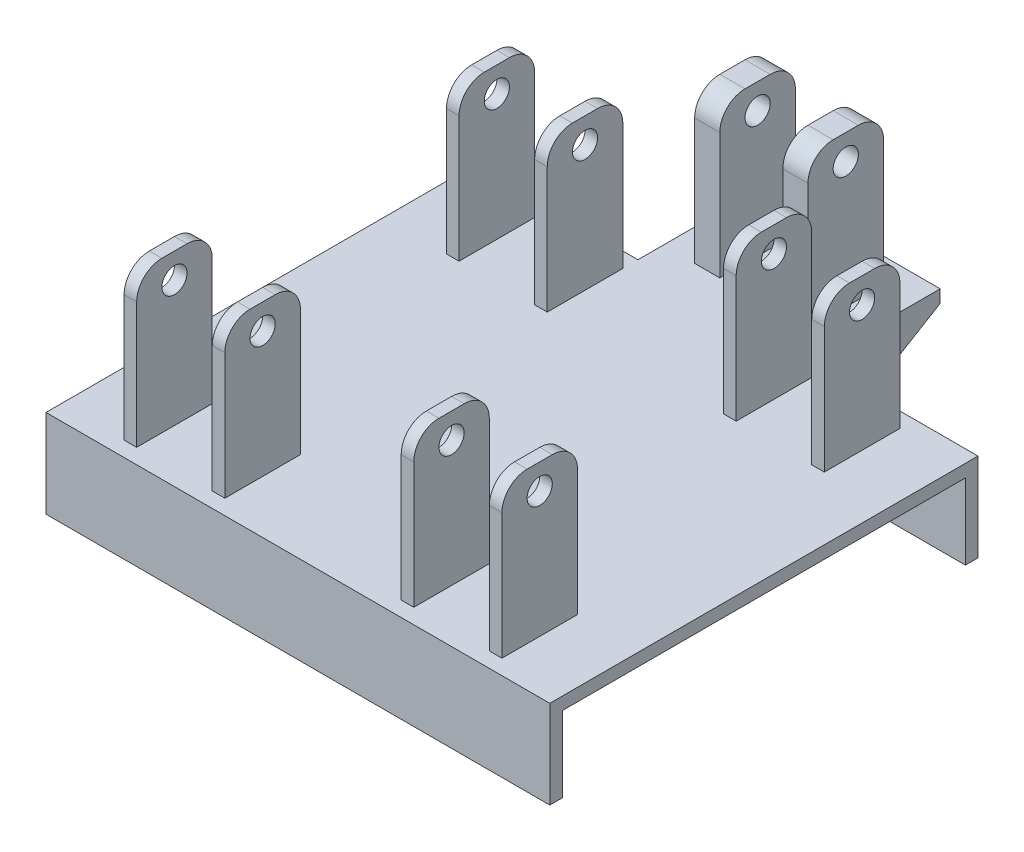
SolidWorks part; units mm, degrees
ref_plane "Front Plane" through (0, 0, 0) normal (0, 0, 1) x (1, 0, 0)
ref_plane "Top Plane" through (0, 0, 0) normal (0, 1, 0) x (1, 0, 0)
ref_plane "Right Plane" through (0, 0, 0) normal (1, 0, 0) x (0, 0, -1)
sketch "Sketch2" plane through (0, 0, 0) normal (0, 1, 0) x (1, 0, 0)
  line L1 (-100, -80) -> (100, -80)
  line L2 (-100, -80) -> (-100, 80)
  line L3 (-100, 80) -> (100, 80)
  line L4 (100, -80) -> (100, 80)
  line L5 (-100, -80) -> (100, 80) construction
  line L6 (-100, 80) -> (100, -80) construction
  point P0 (0, 0)
  dimension "D1" = 160
  dimension "D2" = 200
extrude "Boss-Extrude1" add sketch "Sketch2" along normal blind 5
sketch "Sketch3" plane through (0, 5, 0) normal (0, 1, 0) x (1, 0, 0)
  line L1 (-75, 78.9876) -> (-70, 78.9876)
  line L2 (-75, 78.9876) -> (-75, 48.9876)
  line L3 (-75, 48.9876) -> (-70, 48.9876)
  line L4 (-70, 78.9876) -> (-70, 48.9876)
  line L5 (-75, 78.9876) -> (-70, 48.9876) construction
  line L6 (-75, 48.9876) -> (-70, 78.9876) construction
  line L7 (-40, 78.9876) -> (-35, 78.9876)
  line L8 (-40, 78.9876) -> (-40, 48.9876)
  line L9 (-40, 48.9876) -> (-35, 48.9876)
  line L10 (-35, 78.9876) -> (-35, 48.9876)
  line L11 (-40, 78.9876) -> (-35, 48.9876) construction
  line L12 (-40, 48.9876) -> (-35, 78.9876) construction
  line L13 (-100, 80) -> (-100, -80) construction
  line L14 (600, 63.9876) -> (-100, 63.9876) construction
  point P0 (-72.5, 63.9876)
  point P5 (-37.5, 63.9876)
  point P10 (-72.5, 64.3962)
  dimension "D1" = 5
  dimension "D2" = 30
  dimension "D3" = 30
  dimension "D5" = 25
extrude "Boss-Extrude2" add sketch "Sketch3" along normal blind 60
sketch "Sketch4" plane through (-35, 0, 0) normal (1, 0, 0) x (0, 0, -1)
  line L0 (48.9876, 65) -> (78.9876, 65) construction
  line L1 (78.9876, 65) -> (78.9876, 5) construction
  circle A0 centre (63.9876, 55) radius 5
  dimension "D1" = 10
  dimension "D2" = 10
  dimension "D3" = 15
extrude "Cut-Extrude1" cut sketch "Sketch4" against normal up to surface (40 mm away) up to face at (-75, 35, -63.9876)
fillet "Fillet1" radius 10 4 edges at (-72.5, 65, -78.9876) (-72.5, 65, -48.9876) (-37.5, 65, -48.9876) (-37.5, 65, -78.9876)
pattern_linear "LPattern1" count 2 spacing 110 along (1, 0, 0) count 2 spacing 127.9876 along (0, 0, 1) of "Boss-Extrude2", "Cut-Extrude1", "Fillet1"
sketch "Sketch6" plane through (0, 0, -80) normal (0, 0, -1) x (-1, 0, 0)
  line L0 (-100, 5) -> (-100, 0) construction
  line L1 (-100, 5) -> (100, 5)
  line L2 (-100, 5) -> (-100, -30)
  line L3 (-100, -30) -> (100, -30)
  line L4 (100, 5) -> (100, -30)
  dimension "D1" = 35
extrude "Boss-Extrude3" add sketch "Sketch6" along normal blind 5
mirror "Mirror8" about plane through (0, 0, 0) normal (0, 0, 1) of "Boss-Extrude3"
sketch "Sketch7" plane through (0, 0, -85) normal (0, 0, -1) x (-1, 0, 0)
  line L1 (-35, 5) -> (35, 5)
  line L2 (-35, 5) -> (-35, 0)
  line L3 (-35, 0) -> (35, 0)
  line L4 (35, 5) -> (35, 0)
  dimension "D1" = 5
extrude "Boss-Extrude8" add sketch "Sketch7" along normal blind 50
sketch "Sketch9" plane through (0, 5, 0) normal (0, 1, 0) x (1, 0, 0)
  line L1 (-22.5, 125) -> (-12.5, 125)
  line L2 (-22.5, 125) -> (-22.5, 95)
  line L3 (-22.5, 95) -> (-12.5, 95)
  line L4 (-12.5, 125) -> (-12.5, 95)
  line L5 (12.5, 125) -> (22.5, 125)
  line L6 (12.5, 125) -> (12.5, 95)
  line L7 (12.5, 95) -> (22.5, 95)
  line L8 (22.5, 125) -> (22.5, 95)
  line L9 (-22.5, 110) -> (-35, 110) construction
  line L10 (-35, 135) -> (-35, 85) construction
  line L11 (22.5, 110) -> (35, 110) construction
  line L12 (35, 135) -> (35, 85) construction
  dimension "D1" = 10
  dimension "D2" = 25
  dimension "D3" = 10
  dimension "D4" = 30
extrude "Boss-Extrude9" add sketch "Sketch9" along normal blind 60
fillet "Fillet2" radius 10 4 edges at (17.5, 65, -125) (17.5, 65, -95) (-17.5, 65, -125) (-17.5, 65, -95)
sketch "Sketch11" plane through (22.5, 0, 0) normal (1, 0, 0) x (0, 0, -1)
  line L0 (105, 65) -> (115, 65) construction
  line L1 (125, 55) -> (125, 5) construction
  circle A0 centre (110, 55) radius 5
  dimension "D1" = 10
  dimension "D2" = 10
  dimension "D3" = 15
extrude "Cut-Extrude2" cut sketch "Sketch11" against normal up to surface (45 mm away) up to face at (-22.5, 42.357, -110)
sketch "Sketch14" plane through (35, 0, 0) normal (1, 0, 0) x (0, 0, -1)
  line L0 (135, 0) -> (85, -30)
  line L1 (88, 0) -> (-88, 0) construction
  line L2 (135, 5) -> (135, 0) construction
rib "Rib4" sketch "Sketch14" sketch "Sketch14" thickness 10 extrusion direction parallel to sketch draft on no parameters "D1"=10
mirror "Mirror1" about plane through (0, 0, 0) normal (1, 0, 0) of "Rib4"
